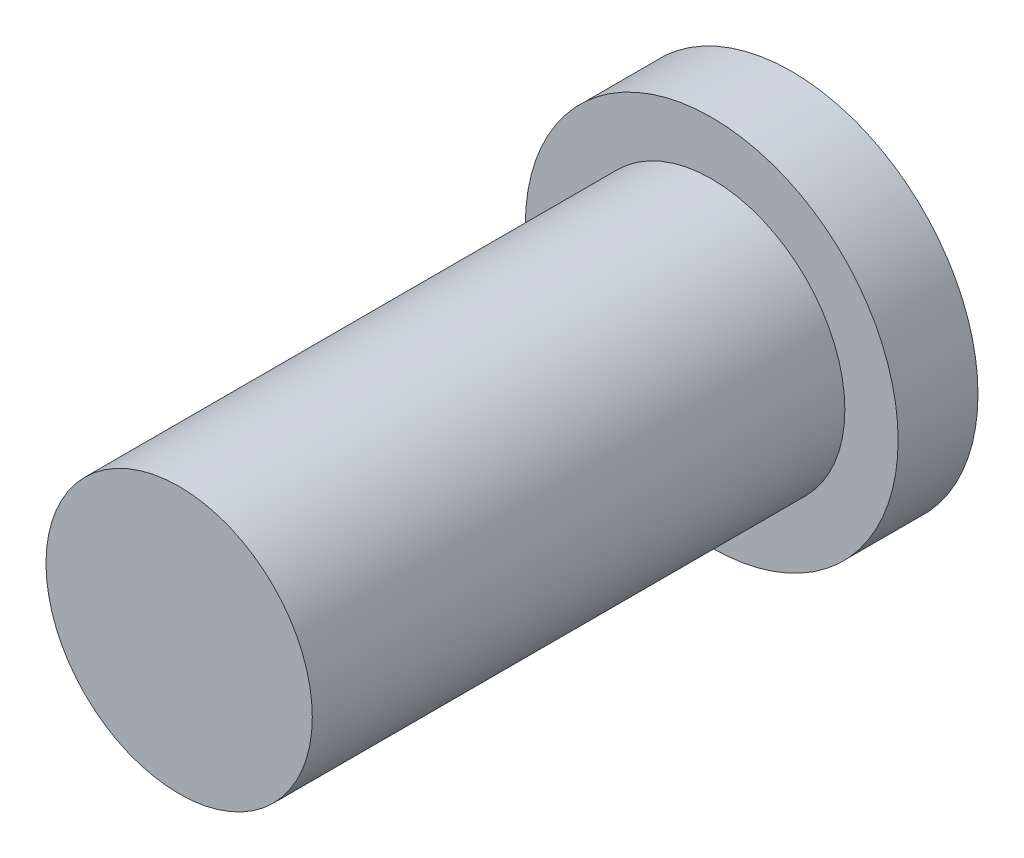
SolidWorks part; units mm, degrees
ref_plane "Ön Düzlem" through (0, 0, 0) normal (0, 0, 1) x (1, 0, 0)
ref_plane "Üst Düzlem" through (0, 0, 0) normal (0, 1, 0) x (1, 0, 0)
ref_plane "Sağ Düzlem" through (0, 0, 0) normal (1, 0, 0) x (0, 0, -1)
sketch "Sketch2" plane through (0, 0, 0) normal (0, 0, 1) x (1, 0, 0)
  circle A0 centre (0, 0) radius 2.5
  dimension "D1" = 5
extrude "Boss-Extrude1" add sketch "Sketch2" along normal blind 10
sketch "Sketch3" plane through (0, 0, 0) normal (0, 0, -1) x (-1, 0, 0)
  circle A0 centre (0, 0) radius 3.5
  dimension "D1" = 7
extrude "Boss-Extrude2" add sketch "Sketch3" along normal blind 1.5
